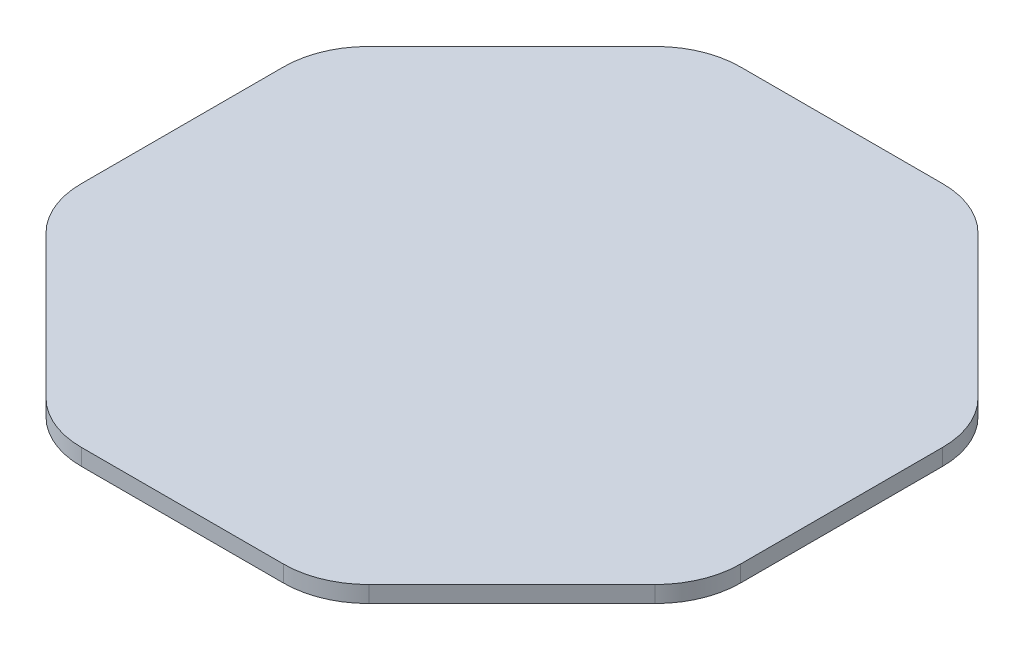
SolidWorks part; units mm, degrees
ref_plane "前视基准面" through (0, 0, 0) normal (0, 0, 1) x (1, 0, 0)
ref_plane "上视基准面" through (0, 0, 0) normal (0, 1, 0) x (1, 0, 0)
ref_plane "右视基准面" through (0, 0, 0) normal (1, 0, 0) x (0, 0, -1)
sketch "草图1" plane through (0, 0, 0) normal (0, 1, 0) x (1, 0, 0)
  line L7 (24.8528, 60) -> (-24.8528, 60)
  line L8 (-24.8528, 60) -> (-60, 24.8528)
  line L9 (-60, 24.8528) -> (-60, -24.8528)
  line L10 (-60, -24.8528) -> (-24.8528, -60)
  line L11 (-24.8528, -60) -> (24.8528, -60)
  line L12 (24.8528, -60) -> (60, -24.8528)
  line L13 (60, -24.8528) -> (60, 24.8528)
  line L14 (60, 24.8528) -> (24.8528, 60)
  circle A0 centre (0, 0) radius 60
  circle A1 centre (0, 0) radius 60 construction
  dimension "D1" = 120
extrude "凸台-拉伸1" add sketch "草图1" along normal blind 3
fillet "圆角1" radius 15.5 8 edges at (60, 1.5, 24.8528) (60, 1.5, -24.8528) (24.8528, 1.5, -60) (-24.8528, 1.5, -60) (-60, 1.5, -24.8528) (-60, 1.5, 24.8528) (-24.8528, 1.5, 60) (24.8528, 1.5, 60)
